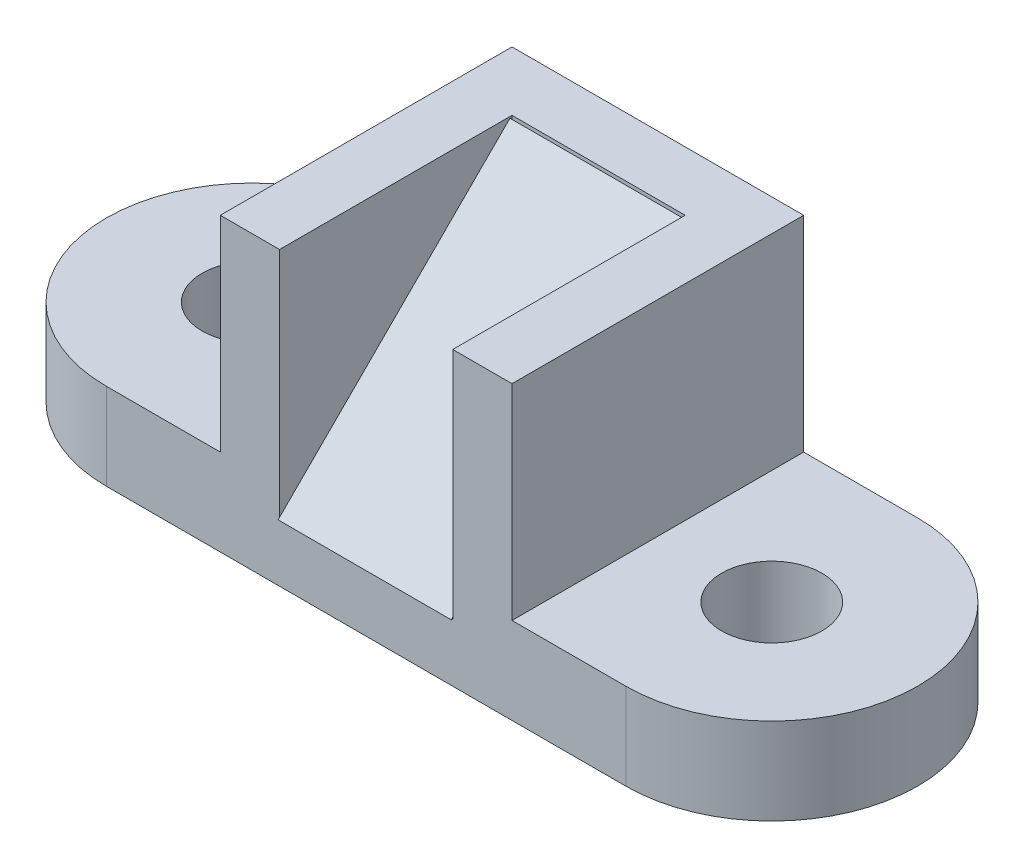
SolidWorks part; units mm, degrees
ref_plane "Front Plane" through (0, 0, 0) normal (0, 0, 1) x (1, 0, 0)
ref_plane "Top Plane" through (0, 0, 0) normal (0, 1, 0) x (1, 0, 0)
ref_plane "Right Plane" through (0, 0, 0) normal (1, 0, 0) x (0, 0, -1)
sketch "Sketch3" plane through (0, 0, 0) normal (0, 1, 0) x (1, 0, 0)
  line L0 (0, 0) -> (114, 0) construction
  line L1 (0, 32) -> (114, 32)
  line L2 (0, -32) -> (114, -32)
  arc A0 (0, 32) -> (0, -32) centre (0, 0) ccw
  arc A1 (114, -32) -> (114, 32) centre (114, 0) ccw
  point P3 (57, 0)
  dimension "D2" = 32
  dimension "D1" = 114
extrude "Boss-Extrude2" add sketch "Sketch3" along normal blind 19
sketch "Sketch4" plane through (0, 19, 0) normal (0, 1, 0) x (1, 0, 0)
  line L0 (57, 32) -> (57, -32) construction
  line L1 (114, 32) -> (0, 32) construction
  line L2 (0, -32) -> (114, -32) construction
  circle A0 centre (0, 0) radius 11
  circle A1 centre (114, 0) radius 11
  dimension "D1" = 22
extrude "Cut-Extrude1" cut sketch "Sketch4" against normal through all
sketch "Sketch5" plane through (0, 19, 0) normal (0, 1, 0) x (1, 0, 0)
  line L0 (57, 32) -> (57, -32) construction
  line L1 (114, 32) -> (0, 32) construction
  line L2 (0, -32) -> (114, -32) construction
  line L4 (25, 32) -> (89, 32)
  line L5 (25, 32) -> (25, -32)
  line L6 (25, -32) -> (89, -32)
  line L7 (89, 32) -> (89, -32)
  line L8 (25, 32) -> (89, -32) construction
  line L9 (25, -32) -> (89, 32) construction
  point P6 (57, 0)
  dimension "D1" = 64
extrude "Boss-Extrude3" add sketch "Sketch5" along normal blind 45
sketch "Sketch6" plane through (0, 0, 32) normal (0, 0, 1) x (1, 0, 0)
  line L0 (25, 64) -> (89, 64) construction
  line L1 (38, 64) -> (76, 64)
  line L2 (38, 64) -> (38, 13)
  line L3 (38, 13) -> (76, 13)
  line L4 (76, 64) -> (76, 13)
  line L5 (0, 0) -> (114, 0) construction
  line L6 (89, 64) -> (89, 19) construction
  line L7 (25, 64) -> (25, 19) construction
  dimension "D1" = 13
  dimension "D2" = 13
  dimension "D3" = 13
extrude "Cut-Extrude2" cut sketch "Sketch6" against normal blind 51
sketch "Sketch8" plane through (38, 0, 0) normal (1, 0, 0) x (0, 0, -1)
  line L0 (18.5495, 63.6667) -> (-32.3297, 12.7875)
  line L1 (-32.3297, 12.7875) -> (18.5495, 15.7729)
  line L2 (18.5495, 15.7729) -> (18.5495, 63.6667)
extrude "Boss-Extrude4" add sketch "Sketch8" along normal blind 38
